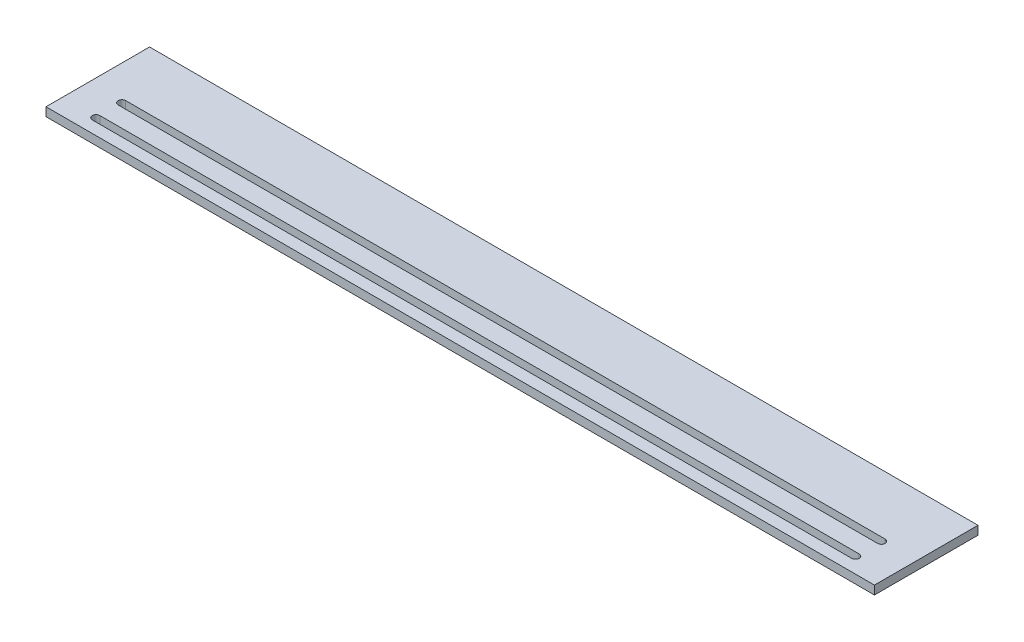
SolidWorks part; units mm, degrees
ref_plane "Front Plane" through (0, 0, 0) normal (0, 0, 1) x (1, 0, 0)
ref_plane "Top Plane" through (0, 0, 0) normal (0, 1, 0) x (1, 0, 0)
ref_plane "Right Plane" through (0, 0, 0) normal (1, 0, 0) x (0, 0, -1)
sketch "Sketch1" plane through (0, 0, 0) normal (0, 1, 0) x (1, 0, 0)
  line L1 (-304.8, -38.1) -> (304.8, -38.1)
  line L2 (-304.8, -38.1) -> (-304.8, 38.1)
  line L3 (-304.8, 38.1) -> (304.8, 38.1)
  line L4 (304.8, -38.1) -> (304.8, 38.1)
  line L5 (-304.8, -38.1) -> (304.8, 38.1) construction
  line L6 (-304.8, 38.1) -> (304.8, -38.1) construction
  point P0 (0, 0)
  point P6 (0, 0)
  dimension "D1" = 609.6
  dimension "D2" = 76.2
extrude "Boss-Extrude1" add sketch "Sketch1" along normal mid plane 6.35
sketch "Sketch2" plane through (0, 3.175, 0) normal (0, 1, 0) x (1, 0, 0)
  line L0 (-279.4, -7.62) -> (279.4, -7.62) construction
  line L1 (-279.4, -4.8419) -> (279.4, -4.8419)
  line L2 (-279.4, -10.3981) -> (279.4, -10.3981)
  line L3 (-304.8, 38.1) -> (-304.8, -38.1) construction
  line L4 (304.8, -38.1) -> (304.8, 38.1) construction
  line L5 (-279.4, -26.67) -> (279.4, -26.67) construction
  line L6 (-279.4, -23.8919) -> (279.4, -23.8919)
  line L7 (-279.4, -29.4481) -> (279.4, -29.4481)
  arc A0 (-279.4, -4.8419) -> (-279.4, -10.3981) centre (-279.4, -7.62) ccw
  arc A1 (279.4, -10.3981) -> (279.4, -4.8419) centre (279.4, -7.62) ccw
  arc A2 (-279.4, -23.8919) -> (-279.4, -29.4481) centre (-279.4, -26.67) ccw
  arc A3 (279.4, -29.4481) -> (279.4, -23.8919) centre (279.4, -26.67) ccw
  point P0 (-248.6319, -26.67)
  point P1 (-248.6319, -7.62)
  point P6 (0, -7.62)
  point P17 (0, -26.67)
  point P22 (0, 0)
  point P23 (0, 0)
  dimension "D1" = 25.4
  dimension "D2" = 25.4
  dimension "D3" = 5.5562
  dimension "D4" = 5.5562
extrude "Cut-Extrude1" cut sketch "Sketch2" against normal through all
